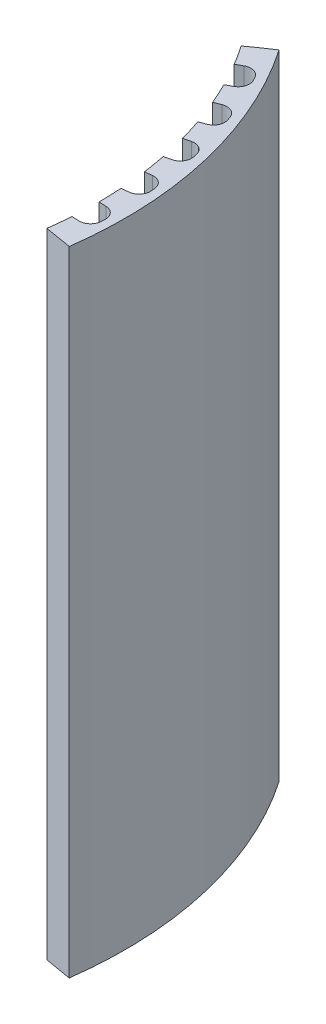
SolidWorks part; units mm, degrees
material "AISI 304"
ref_plane "Plano frontal" through (0, 0, 0) normal (0, 0, 1) x (1, 0, 0)
ref_plane "Plano superior" through (0, 0, 0) normal (0, 1, 0) x (1, 0, 0)
ref_plane "Plano direito" through (0, 0, 0) normal (1, 0, 0) x (0, 0, -1)
sketch "Esboço1" plane through (0, 0, 0) normal (0, 1, 0) x (1, 0, 0)
  line L14 (10.7605, 7.3508) -> (10.9692, 7.5046)
  line L16 (11.6442, 5.851) -> (11.8716, 5.9756)
  line L17 (11.1973, 6.6665) -> (11.4246, 6.7911)
  line L18 (12.3202, 4.2467) -> (12.5621, 4.3399)
  line L19 (11.9859, 5.1146) -> (12.2279, 5.2078)
  line L20 (12.7763, 2.5667) -> (13.0285, 2.6268)
  line L21 (12.5607, 3.4714) -> (12.8129, 3.5315)
  line L22 (13.0044, 0.8409) -> (13.2624, 0.8669)
  line L23 (12.9113, 1.7662) -> (13.1693, 1.7922)
  line L24 (13.0005, -0.8999) -> (13.2596, -0.9086)
  line L25 (13.0315, 0.0296) -> (13.2906, 0.0209)
  line L27 (12.9192, -1.7076) -> (13.1748, -1.7507)
  line L108 (11.0822, 8.0197) -> (11.3418, 8.2075)
  line L129 (13.5078, -2.1657) -> (13.8235, -2.2163)
  arc A28 (10.9692, 7.5046) -> (11.0822, 8.0197) centre (10.7319, 7.8266) ccw
  arc A30 (12.0311, 6.5168) -> (11.9667, 6.6343) centre (0, 0) ccw
  arc A31 (11.8716, 5.9756) -> (12.0311, 6.5168) centre (11.6793, 6.3263) ccw
  arc A32 (11.9667, 6.6343) -> (11.4246, 6.7911) centre (11.6169, 6.4403) ccw
  arc A33 (12.7923, 4.8551) -> (12.7442, 4.9801) centre (0, 0) ccw
  arc A34 (12.5621, 4.3399) -> (12.7923, 4.8551) centre (12.4183, 4.7132) ccw
  arc A35 (12.7442, 4.9801) -> (12.2279, 5.2078) centre (12.3716, 4.8345) ccw
  arc A36 (13.3253, 3.1067) -> (13.2943, 3.237) centre (0, 0) ccw
  arc A37 (13.0285, 2.6268) -> (13.3253, 3.1067) centre (12.9357, 3.0159) ccw
  arc A38 (13.2943, 3.237) -> (12.8129, 3.5315) centre (12.9056, 3.1424) ccw
  arc A39 (13.6205, 1.3029) -> (13.6071, 1.4362) centre (0, 0) ccw
  arc A40 (13.2624, 0.8669) -> (13.6205, 1.3029) centre (13.2223, 1.2648) ccw
  arc A41 (13.6071, 1.4362) -> (13.1693, 1.7922) centre (13.2093, 1.3942) ccw
  arc A42 (13.6726, -0.5241) -> (13.6771, -0.3903) centre (0, 0) ccw
  arc A43 (13.2596, -0.9086) -> (13.6726, -0.5241) centre (13.2729, -0.5088) ccw
  arc A44 (13.6771, -0.3903) -> (13.2906, 0.0209) centre (13.2773, -0.3789) ccw
  arc A47 (13.5078, -2.1657) -> (13.1748, -1.7507) centre (13.1083, -2.1452) ccw
  arc A163 (11.1973, 6.6665) -> (10.7605, 7.3508) centre (0, 0) ccw
  arc A164 (11.9859, 5.1146) -> (11.6442, 5.851) centre (0, 0) ccw
  arc A165 (12.5607, 3.4714) -> (12.3202, 4.2467) centre (0, 0) ccw
  arc A166 (12.9113, 1.7662) -> (12.7763, 2.5667) centre (0, 0) ccw
  arc A167 (13.0315, 0.0296) -> (13.0044, 0.8409) centre (0, 0) ccw
  arc A168 (12.9192, -1.7076) -> (13.0005, -0.8999) centre (0, 0) ccw
  arc A248 (13.8235, -2.2163) -> (11.3418, 8.2075) centre (0, 0) ccw
  point P4 (0.475, 0)
  point P5 (0, 13.6827)
  point P6 (0.475, 14)
  point P7 (-0.475, 0)
  point P8 (-0.475, 14)
extrude "Ressalto-extrusão1" add sketch "Esboço1" along normal blind 22.5
sketch "Esboço2" plane through (0, 22.5, 0) normal (0, 1, 0) x (1, 0, 0)
  line L0 (13.1748, -1.7507) -> (13.8747, -1.8688)
  line L1 (10.9692, 7.5046) -> (11.5546, 7.9051)
  line L15 (10.9692, 7.5046) -> (10.7605, 7.3508)
  line L16 (11.1973, 6.6665) -> (11.4246, 6.7911)
  line L17 (11.8716, 5.9756) -> (11.6442, 5.851)
  line L18 (11.9859, 5.1146) -> (12.2279, 5.2078)
  line L19 (12.5621, 4.3399) -> (12.3202, 4.2467)
  line L20 (12.5607, 3.4714) -> (12.8129, 3.5315)
  line L21 (13.0285, 2.6268) -> (12.7763, 2.5667)
  line L22 (12.9113, 1.7662) -> (13.1693, 1.7922)
  line L23 (13.2624, 0.8669) -> (13.0044, 0.8409)
  line L24 (13.0315, 0.0296) -> (13.2906, 0.0209)
  line L25 (13.2596, -0.9086) -> (13.0005, -0.8999)
  line L26 (12.9192, -1.7076) -> (13.1748, -1.7507)
  line L27 (13.5078, -2.1657) -> (13.8235, -2.2163)
  line L28 (11.3418, 8.2075) -> (11.0822, 8.0197)
  line L41 (13.5078, -2.1657) -> (13.8235, -2.2163)
  line L42 (11.3418, 8.2075) -> (11.0822, 8.0197)
  arc A1 (11.5546, 7.9051) -> (11.3418, 8.2075) centre (0, 0) ccw
  arc A25 (10.9692, 7.5046) -> (11.0822, 8.0197) centre (10.7319, 7.8266) ccw
  arc A26 (11.1973, 6.6665) -> (10.7605, 7.3508) centre (0, 0) ccw
  arc A27 (11.9667, 6.6343) -> (11.4246, 6.7911) centre (11.6169, 6.4403) ccw
  arc A28 (12.0311, 6.5168) -> (11.9667, 6.6343) centre (0, 0) ccw
  arc A29 (11.8716, 5.9756) -> (12.0311, 6.5168) centre (11.6793, 6.3263) ccw
  arc A30 (11.9859, 5.1146) -> (11.6442, 5.851) centre (0, 0) ccw
  arc A31 (12.7442, 4.9801) -> (12.2279, 5.2078) centre (12.3716, 4.8345) ccw
  arc A32 (12.7923, 4.8551) -> (12.7442, 4.9801) centre (0, 0) ccw
  arc A33 (12.5621, 4.3399) -> (12.7923, 4.8551) centre (12.4183, 4.7132) ccw
  arc A34 (12.5607, 3.4714) -> (12.3202, 4.2467) centre (0, 0) ccw
  arc A35 (13.2943, 3.237) -> (12.8129, 3.5315) centre (12.9056, 3.1424) ccw
  arc A36 (13.3253, 3.1067) -> (13.2943, 3.237) centre (0, 0) ccw
  arc A37 (13.0285, 2.6268) -> (13.3253, 3.1067) centre (12.9357, 3.0159) ccw
  arc A38 (12.9113, 1.7662) -> (12.7763, 2.5667) centre (0, 0) ccw
  arc A39 (13.6071, 1.4362) -> (13.1693, 1.7922) centre (13.2093, 1.3942) ccw
  arc A40 (13.6205, 1.3029) -> (13.6071, 1.4362) centre (0, 0) ccw
  arc A41 (13.2624, 0.8669) -> (13.6205, 1.3029) centre (13.2223, 1.2648) ccw
  arc A42 (13.0315, 0.0296) -> (13.0044, 0.8409) centre (0, 0) ccw
  arc A43 (13.6771, -0.3903) -> (13.2906, 0.0209) centre (13.2773, -0.3789) ccw
  arc A44 (13.6726, -0.5241) -> (13.6771, -0.3903) centre (0, 0) ccw
  arc A45 (13.2596, -0.9086) -> (13.6726, -0.5241) centre (13.2729, -0.5088) ccw
  arc A46 (12.9192, -1.7076) -> (13.0005, -0.8999) centre (0, 0) ccw
  arc A47 (13.5078, -2.1657) -> (13.1748, -1.7507) centre (13.1083, -2.1452) ccw
  arc A48 (13.8235, -2.2163) -> (11.3418, 8.2075) centre (0, 0) ccw
  arc A49 (10.9692, 7.5046) -> (11.0822, 8.0197) centre (10.7319, 7.8266) ccw
  arc A71 (13.5078, -2.1657) -> (13.1748, -1.7507) centre (13.1083, -2.1452) ccw
  arc A72 (13.8235, -2.2163) -> (13.8747, -1.8688) centre (0, 0) ccw
  dimension "D1" = 0
extrude "Corte-extrusão1" cut sketch "Esboço2" against normal through all
